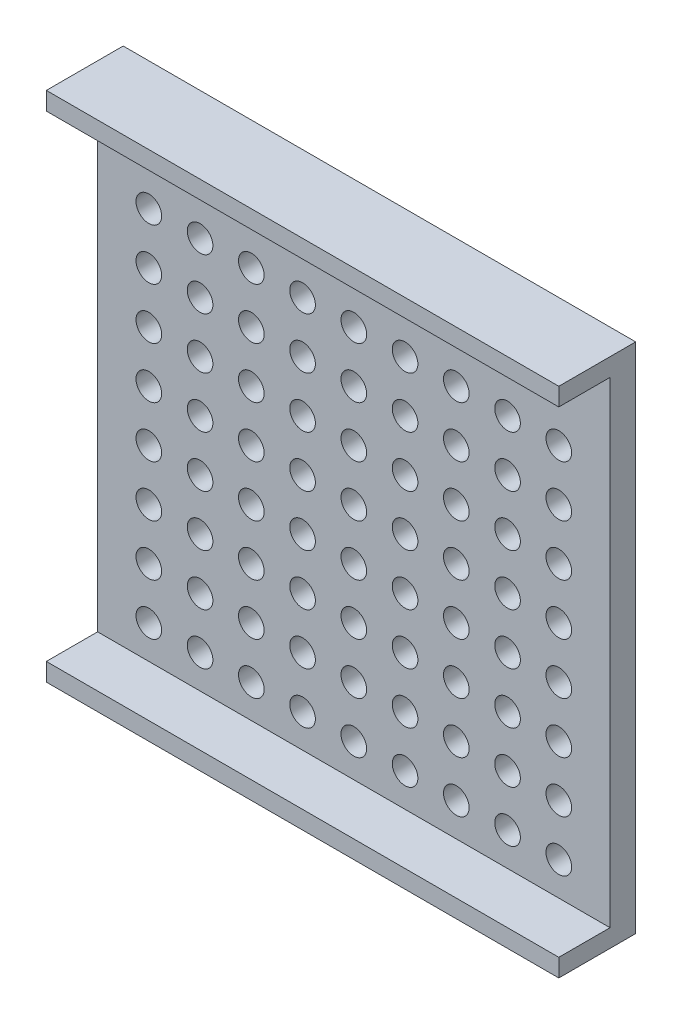
SolidWorks part; units mm, degrees
ref_plane "Front Plane" through (0, 0, 0) normal (0, 0, 1) x (1, 0, 0)
ref_plane "Top Plane" through (0, 0, 0) normal (0, 1, 0) x (1, 0, 0)
ref_plane "Right Plane" through (0, 0, 0) normal (1, 0, 0) x (0, 0, -1)
sketch "Sketch1" plane through (0, 0, 0) normal (0, 0, 1) x (1, 0, 0)
  line L1 (-50, -50) -> (50, -50)
  line L2 (-50, -50) -> (-50, 50)
  line L3 (-50, 50) -> (50, 50)
  line L4 (50, -50) -> (50, 50)
  line L5 (-50, -50) -> (50, 50) construction
  line L6 (-50, 50) -> (50, -50) construction
  circle A0 centre (-40, 40) radius 2.5
  circle A1 centre (-30, 40) radius 2.5
  circle A2 centre (-20, 40) radius 2.5
  circle A3 centre (-10, 40) radius 2.5
  circle A4 centre (0, 40) radius 2.5
  circle A5 centre (10, 40) radius 2.5
  circle A6 centre (20, 40) radius 2.5
  circle A7 centre (30, 40) radius 2.5
  circle A8 centre (40, 40) radius 2.5
  circle A9 centre (-40, 30) radius 2.5
  circle A10 centre (-30, 30) radius 2.5
  circle A11 centre (-20, 30) radius 2.5
  circle A12 centre (-10, 30) radius 2.5
  circle A13 centre (0, 30) radius 2.5
  circle A14 centre (10, 30) radius 2.5
  circle A15 centre (20, 30) radius 2.5
  circle A16 centre (30, 30) radius 2.5
  circle A17 centre (40, 30) radius 2.5
  circle A18 centre (-40, 20) radius 2.5
  circle A19 centre (-30, 20) radius 2.5
  circle A20 centre (-20, 20) radius 2.5
  circle A21 centre (-10, 20) radius 2.5
  circle A22 centre (0, 20) radius 2.5
  circle A23 centre (10, 20) radius 2.5
  circle A24 centre (20, 20) radius 2.5
  circle A25 centre (30, 20) radius 2.5
  circle A26 centre (40, 20) radius 2.5
  circle A27 centre (-40, 10) radius 2.5
  circle A28 centre (-30, 10) radius 2.5
  circle A29 centre (-20, 10) radius 2.5
  circle A30 centre (-10, 10) radius 2.5
  circle A31 centre (0, 10) radius 2.5
  circle A32 centre (10, 10) radius 2.5
  circle A33 centre (20, 10) radius 2.5
  circle A34 centre (30, 10) radius 2.5
  circle A35 centre (40, 10) radius 2.5
  circle A36 centre (-40, 0) radius 2.5
  circle A37 centre (-30, 0) radius 2.5
  circle A38 centre (-20, 0) radius 2.5
  circle A39 centre (-10, 0) radius 2.5
  circle A40 centre (0, 0) radius 2.5
  circle A41 centre (10, 0) radius 2.5
  circle A42 centre (20, 0) radius 2.5
  circle A43 centre (30, 0) radius 2.5
  circle A44 centre (40, 0) radius 2.5
  circle A45 centre (-40, -10) radius 2.5
  circle A46 centre (-30, -10) radius 2.5
  circle A47 centre (-20, -10) radius 2.5
  circle A48 centre (-10, -10) radius 2.5
  circle A49 centre (0, -10) radius 2.5
  circle A50 centre (10, -10) radius 2.5
  circle A51 centre (20, -10) radius 2.5
  circle A52 centre (30, -10) radius 2.5
  circle A53 centre (40, -10) radius 2.5
  circle A54 centre (-40, -20) radius 2.5
  circle A55 centre (-30, -20) radius 2.5
  circle A56 centre (-20, -20) radius 2.5
  circle A57 centre (-10, -20) radius 2.5
  circle A58 centre (0, -20) radius 2.5
  circle A59 centre (10, -20) radius 2.5
  circle A60 centre (20, -20) radius 2.5
  circle A61 centre (30, -20) radius 2.5
  circle A62 centre (40, -20) radius 2.5
  circle A63 centre (-40, -30) radius 2.5
  circle A64 centre (-30, -30) radius 2.5
  circle A65 centre (-20, -30) radius 2.5
  circle A66 centre (-10, -30) radius 2.5
  circle A67 centre (0, -30) radius 2.5
  circle A68 centre (10, -30) radius 2.5
  circle A69 centre (20, -30) radius 2.5
  circle A70 centre (30, -30) radius 2.5
  circle A71 centre (40, -30) radius 2.5
  circle A72 centre (-40, -40) radius 2.5
  circle A73 centre (-30, -40) radius 2.5
  circle A74 centre (-20, -40) radius 2.5
  circle A75 centre (-10, -40) radius 2.5
  circle A76 centre (0, -40) radius 2.5
  circle A77 centre (10, -40) radius 2.5
  circle A78 centre (20, -40) radius 2.5
  circle A79 centre (30, -40) radius 2.5
  circle A80 centre (40, -40) radius 2.5
  point P0 (0, 0)
  dimension "D3" = 5
  dimension "D5" = 10
  dimension "D1" = 100
  dimension "D2" = 100
  dimension "D4" = 10
  dimension "D6" = 9
  dimension "D7" = 9
extrude "Boss-Extrude1" add sketch "Sketch1" along normal blind 5
sketch "Sketch2" plane through (0, 0, 5) normal (0, 0, 1) x (1, 0, 0)
  line L0 (50, -50) -> (50, 50) construction
  line L1 (-50, 50) -> (50, 50)
  line L2 (-50, 50) -> (-50, 46.5)
  line L3 (-50, 46.5) -> (50, 46.5)
  line L4 (50, 50) -> (50, 46.5)
  line L6 (-50, -50) -> (50, -50)
  line L7 (-50, -50) -> (-50, -46.5)
  line L8 (-50, -46.5) -> (50, -46.5)
  line L9 (50, -50) -> (50, -46.5)
  dimension "D1" = 3.5
  dimension "D2" = 3.5
extrude "Boss-Extrude2" add sketch "Sketch2" along normal blind 10
